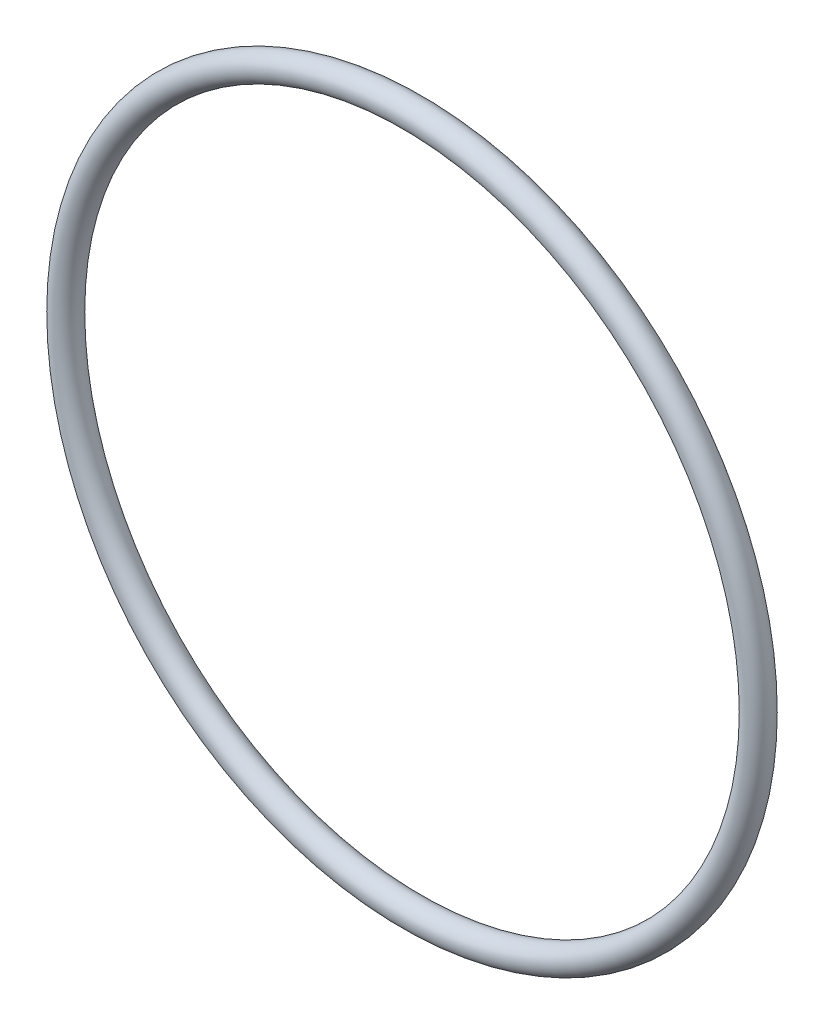
SolidWorks part; units mm, degrees
ref_plane "Front" through (0, 0, 0) normal (0, 0, 1) x (1, 0, 0)
ref_plane "Top" through (0, 0, 0) normal (0, 1, 0) x (1, 0, 0)
ref_plane "Right" through (0, 0, 0) normal (1, 0, 0) x (0, 0, -1)
sketch "Sketch1" plane through (0, 0, 0) normal (1, 0, 0) x (0, -1, 0)
  line L0 (0, -1.3081) -> (0, 1.3081) construction
  line L2 (-38.5013, 0) -> (38.5013, 0) construction
  line L3 (-32.385, 0) -> (32.385, 0) construction
  circle A0 centre (33.6931, 0) radius 1.3081
  point P9 (32.385, 0)
  point P10 (35.0012, 0)
  point P13 (33.6931, 1.3081)
  point P14 (33.6931, -1.3081)
  dimension "Width" = 2.6162
  dimension "ID" = 64.77
revolve "Revolve1" add sketch "Sketch1" angle 360 about L0
